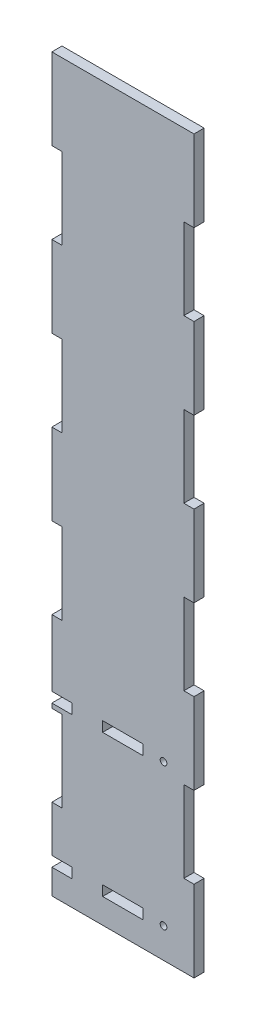
SolidWorks part; units mm, degrees
ref_plane "Front Plane" through (0, 0, 0) normal (0, 0, 1) x (1, 0, 0)
ref_plane "Top Plane" through (0, 0, 0) normal (0, 1, 0) x (1, 0, 0)
ref_plane "Right Plane" through (0, 0, 0) normal (1, 0, 0) x (0, 0, -1)
sketch "Sketch2" plane through (0, 0, 0) normal (0, 1, 0) x (0, 0, 1)
  line L1 (38.1, -44.45) -> (44.45, -44.45)
  line L2 (38.1, -44.45) -> (38.1, 44.45)
  line L3 (38.1, 44.45) -> (44.45, 44.45)
  line L4 (44.45, -44.45) -> (44.45, 44.45)
  dimension "D1" = 88.9
  dimension "D2" = 6.35
extrude "Boss-Extrude1" add sketch "Sketch2" along normal blind 457.2
ref_plane "Plane1" through (0, 0, 0) normal (1, 0, 0) x (0, 0, -1)
sketch "Sketch4" plane through (0, 0, 44.45) normal (0, 0, 1) x (1, 0, 0)
  line L0 (44.45, 457.2) -> (44.45, 406.4) construction
  line L1 (44.45, 457.2) -> (44.45, 0) construction
  line L2 (44.45, 406.4) -> (44.45, 355.6) construction
  line L3 (44.45, 355.6) -> (44.45, 304.8) construction
  line L4 (44.45, 304.8) -> (44.45, 254) construction
  line L5 (44.45, 254) -> (44.45, 203.2) construction
  line L6 (44.45, 203.2) -> (44.45, 152.4) construction
  line L7 (44.45, 152.4) -> (44.45, 101.6) construction
  line L8 (44.45, 101.6) -> (44.45, 50.8) construction
  line L9 (44.45, 50.8) -> (44.45, 0) construction
  line L11 (44.45, 406.4) -> (38.1, 406.4)
  line L12 (44.45, 406.4) -> (44.45, 355.6)
  line L13 (44.45, 355.6) -> (38.1, 355.6)
  line L14 (38.1, 406.4) -> (38.1, 355.6)
  line L15 (44.45, 304.8) -> (38.1, 304.8)
  line L16 (44.45, 304.8) -> (44.45, 254)
  line L17 (44.45, 254) -> (38.1, 254)
  line L18 (38.1, 304.8) -> (38.1, 254)
  line L19 (44.45, 203.2) -> (38.1, 203.2)
  line L20 (44.45, 203.2) -> (44.45, 152.4)
  line L21 (44.45, 152.4) -> (38.1, 152.4)
  line L22 (38.1, 203.2) -> (38.1, 152.4)
  line L23 (44.45, 101.6) -> (38.1, 101.6)
  line L24 (44.45, 101.6) -> (44.45, 50.8)
  line L25 (44.45, 50.8) -> (38.1, 50.8)
  line L26 (38.1, 101.6) -> (38.1, 50.8)
  dimension "D1" = 6.35
extrude "Cut-Extrude1" cut sketch "Sketch4" against normal through all
mirror "Mirror1" about plane through (0, 0, 0) normal (1, 0, 0) of "Cut-Extrude1"
sketch "Sketch5" plane through (0, 0, 38.1) normal (0, 0, -1) x (-1, 0, 0)
  line L0 (0, 0) -> (0, 124.5607) construction
  line L1 (-12.7, 110.8375) -> (12.7, 110.8375)
  line L2 (-12.7, 110.8375) -> (-12.7, 104.4875)
  line L3 (-12.7, 104.4875) -> (12.7, 104.4875)
  line L4 (12.7, 110.8375) -> (12.7, 104.4875)
  line L5 (-12.7, 21.9375) -> (12.7, 21.9375)
  line L6 (-12.7, 21.9375) -> (-12.7, 15.5875)
  line L7 (-12.7, 15.5875) -> (12.7, 15.5875)
  line L8 (12.7, 21.9375) -> (12.7, 15.5875)
  line L36 (38.1, 101.6) -> (44.45, 101.6)
  line L37 (44.45, 101.6) -> (44.45, 152.4)
  line L38 (44.45, 152.4) -> (38.1, 152.4)
  line L39 (38.1, 152.4) -> (38.1, 203.2)
  line L40 (38.1, 203.2) -> (44.45, 203.2)
  line L41 (44.45, 203.2) -> (44.45, 254)
  line L42 (44.45, 254) -> (38.1, 254)
  line L43 (38.1, 254) -> (38.1, 304.8)
  line L44 (38.1, 304.8) -> (44.45, 304.8)
  line L45 (44.45, 304.8) -> (44.45, 355.6)
  line L46 (44.45, 355.6) -> (38.1, 355.6)
  line L47 (38.1, 355.6) -> (38.1, 406.4)
  line L48 (38.1, 406.4) -> (44.45, 406.4)
  line L49 (44.45, 406.4) -> (44.45, 457.2)
  line L50 (44.45, 457.2) -> (-44.45, 457.2)
  line L51 (-44.45, 457.2) -> (-44.45, 406.4)
  line L52 (-44.45, 406.4) -> (-38.1, 406.4)
  line L53 (-38.1, 406.4) -> (-38.1, 355.6)
  line L54 (-38.1, 355.6) -> (-44.45, 355.6)
  line L55 (-44.45, 355.6) -> (-44.45, 304.8)
  line L56 (-44.45, 304.8) -> (-38.1, 304.8)
  line L57 (-38.1, 304.8) -> (-38.1, 254)
  line L58 (-38.1, 254) -> (-44.45, 254)
  line L59 (-44.45, 254) -> (-44.45, 203.2)
  line L60 (-44.45, 203.2) -> (-38.1, 203.2)
  line L61 (-38.1, 203.2) -> (-38.1, 152.4)
  line L62 (-38.1, 152.4) -> (-44.45, 152.4)
  line L63 (-44.45, 152.4) -> (-44.45, 101.6)
  line L64 (-44.45, 101.6) -> (-38.1, 101.6)
  line L65 (-38.1, 101.6) -> (-38.1, 50.8)
  line L66 (-38.1, 50.8) -> (-44.45, 50.8)
  line L67 (-44.45, 50.8) -> (-44.45, 0)
  line L68 (-44.45, 0) -> (44.45, 0)
  line L69 (44.45, 0) -> (44.45, 50.8)
  line L70 (44.45, 50.8) -> (38.1, 50.8)
  line L71 (38.1, 50.8) -> (38.1, 101.6)
  line L72 (38.1, 101.6) -> (44.45, 101.6)
  line L73 (44.45, 101.6) -> (44.45, 152.4)
  line L74 (44.45, 152.4) -> (38.1, 152.4)
  line L75 (38.1, 152.4) -> (38.1, 203.2)
  line L76 (38.1, 203.2) -> (44.45, 203.2)
  line L77 (44.45, 203.2) -> (44.45, 254)
  line L78 (44.45, 254) -> (38.1, 254)
  line L79 (38.1, 254) -> (38.1, 304.8)
  line L80 (38.1, 304.8) -> (44.45, 304.8)
  line L81 (44.45, 304.8) -> (44.45, 355.6)
  line L82 (44.45, 355.6) -> (38.1, 355.6)
  line L83 (38.1, 355.6) -> (38.1, 406.4)
  line L84 (38.1, 406.4) -> (44.45, 406.4)
  line L85 (44.45, 406.4) -> (44.45, 457.2)
  line L86 (44.45, 457.2) -> (-44.45, 457.2)
  line L87 (-44.45, 457.2) -> (-44.45, 406.4)
  line L88 (-44.45, 406.4) -> (-38.1, 406.4)
  line L89 (-38.1, 406.4) -> (-38.1, 355.6)
  line L90 (-38.1, 355.6) -> (-44.45, 355.6)
  line L91 (-44.45, 355.6) -> (-44.45, 304.8)
  line L92 (-44.45, 304.8) -> (-38.1, 304.8)
  line L93 (-38.1, 304.8) -> (-38.1, 254)
  line L94 (-38.1, 254) -> (-44.45, 254)
  line L95 (-44.45, 254) -> (-44.45, 203.2)
  line L96 (-44.45, 203.2) -> (-38.1, 203.2)
  line L97 (-38.1, 203.2) -> (-38.1, 152.4)
  line L98 (-38.1, 152.4) -> (-44.45, 152.4)
  line L99 (-44.45, 152.4) -> (-44.45, 101.6)
  line L100 (-44.45, 101.6) -> (-38.1, 101.6)
  line L101 (-38.1, 101.6) -> (-38.1, 50.8)
  line L102 (-38.1, 50.8) -> (-44.45, 50.8)
  line L103 (-44.45, 50.8) -> (-44.45, 0)
  line L104 (-44.45, 0) -> (44.45, 0)
  line L105 (44.45, 0) -> (44.45, 50.8)
  line L106 (44.45, 50.8) -> (38.1, 50.8)
  line L107 (38.1, 50.8) -> (38.1, 101.6)
  dimension "D2" = 6.35
  dimension "D3" = 6.35
  dimension "D4" = 25.4
  dimension "D5" = 25.4
  dimension "D6" = 82.55
  dimension "D7" = 15.5875
  dimension "D1" = 0
extrude "Cut-Extrude2" cut sketch "Sketch5" against normal through all contours L0 L7 L8 L5 | L7 L0 L5 L6 | L0 L3 L4 L1 | L3 L0 L1 L2
sketch "Sketch6" plane through (0, 0, 44.45) normal (0, 0, 1) x (1, 0, 0)
  line L0 (25.4, 107.6625) -> (-25.4, 107.6625) construction
  line L1 (12.7, 110.8375) -> (-12.7, 110.8375) construction
  line L2 (12.7, 104.4875) -> (-12.7, 104.4875) construction
  line L3 (-25.4, 18.7625) -> (25.4, 18.7625) construction
  line L4 (12.7, 21.9375) -> (-12.7, 21.9375) construction
  line L5 (12.7, 15.5875) -> (-12.7, 15.5875) construction
  line L6 (0, 132.4794) -> (0, 71.8673) construction
  line L7 (-12.7, 110.8375) -> (-12.7, 104.4875) construction
  line L8 (12.7, 110.8375) -> (12.7, 104.4875) construction
  circle A0 centre (25.4, 107.6625) radius 2.0955
  circle A3 centre (25.4, 18.7625) radius 2.0955
  dimension "D1" = 4.191
  dimension "D2" = 12.7
extrude "Cut-Extrude3" cut sketch "Sketch6" against normal through all
sketch "Sketch7" plane through (0, 0, 38.1) normal (0, 0, -1) x (-1, 0, 0)
  line L0 (44.45, 152.4) -> (44.45, 101.6) construction
  line L1 (31.75, 110.8375) -> (44.45, 110.8375)
  line L2 (31.75, 110.8375) -> (31.75, 104.4875)
  line L3 (31.75, 104.4875) -> (44.45, 104.4875)
  line L4 (44.45, 110.8375) -> (44.45, 104.4875)
extrude "Cut-Extrude4" cut sketch "Sketch7" against normal blind 10
sketch "Sketch8" plane through (0, 0, 38.1) normal (0, 0, -1) x (-1, 0, 0)
  line L0 (44.45, 50.8) -> (44.45, 0) construction
  line L1 (31.75, 21.9375) -> (44.45, 21.9375)
  line L2 (31.75, 21.9375) -> (31.75, 15.5875)
  line L3 (31.75, 15.5875) -> (44.45, 15.5875)
  line L4 (44.45, 21.9375) -> (44.45, 15.5875)
extrude "Cut-Extrude5" cut sketch "Sketch8" against normal through all
